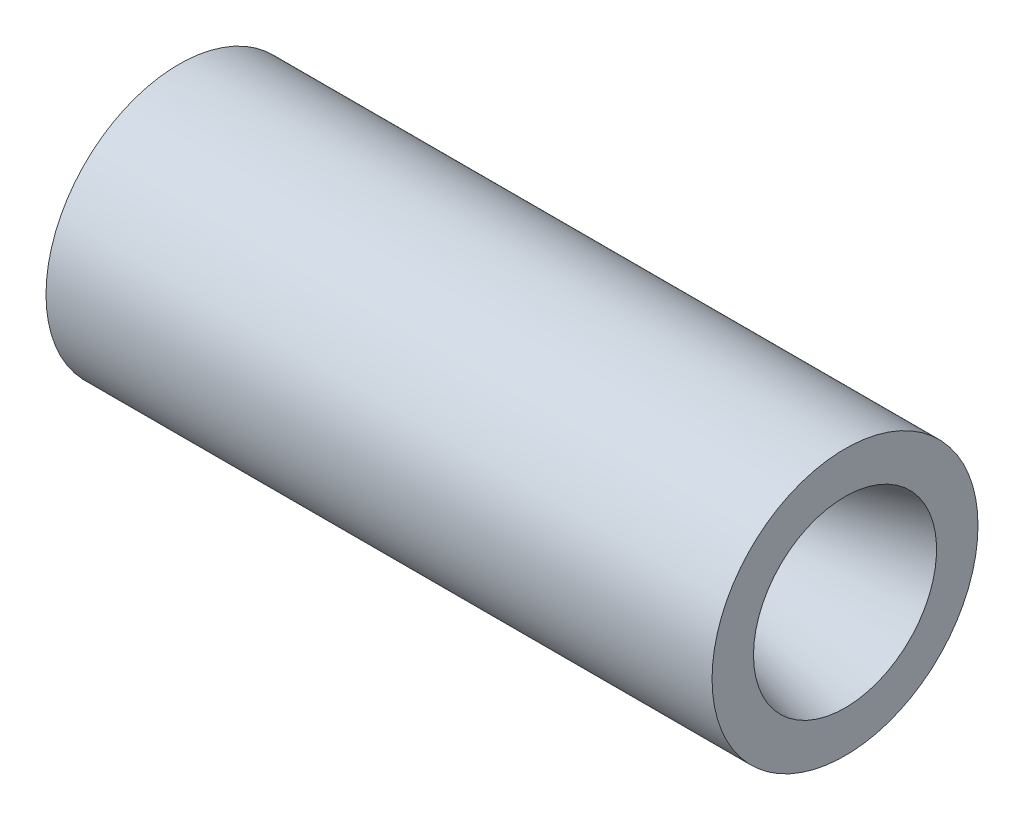
SolidWorks part; units mm, degrees
ref_plane "Front Plane" through (0, 0, 0) normal (0, 0, 1) x (1, 0, 0)
ref_plane "Top Plane" through (0, 0, 0) normal (0, 1, 0) x (1, 0, 0)
ref_plane "Right Plane" through (0, 0, 0) normal (1, 0, 0) x (0, 0, -1)
sketch "Sketch1" plane through (0, 0, 0) normal (0, 0, 1) x (1, 0, 0)
  line L0 (0, 0) -> (0, 43.2766) construction
  line L1 (0, 43.2766) -> (142.9669, 43.2766)
  line L2 (152.7031, 40.2068) -> (181.4981, 20.0443)
  line L3 (195.6276, 17.5529) -> (267.1743, 36.7237)
  line L4 (267.1743, 36.7237) -> (267.1743, 53.34)
  line L5 (267.1743, 53.34) -> (0, 53.34)
  line L6 (0, 53.34) -> (0, 43.2766)
  line L7 (0, 16.9745) -> (267.1743, 16.9745) construction
  line L8 (267.1743, 16.9745) -> (267.1743, 36.7237) construction
  line L9 (0, 0) -> (267.1743, 0) construction
  line L10 (267.1743, 0) -> (267.1743, 16.9745) construction
  arc A0 (142.9669, 43.2766) -> (152.7031, 40.2068) centre (142.9669, 26.3021) cw
  arc A1 (181.4981, 20.0443) -> (195.6276, 17.5529) centre (191.2343, 33.9489) ccw
  dimension "Throat Curve Radius" = 16.9745
  dimension "Overall Radius" = 53.34
  dimension "Combustion Chamber Length" = 142.9669
  dimension "Combustion Inner Radius" = 43.2766
  dimension "Nozzle Exit Radius" = 36.7237
  dimension "Nozzle Throat Radius" = 16.9745
  dimension "Nozzle Exit Degree" = 15
  dimension "Nozzle Top Degree" = 35
revolve "Revolve2" add sketch "Sketch1" angle 360 about L9
